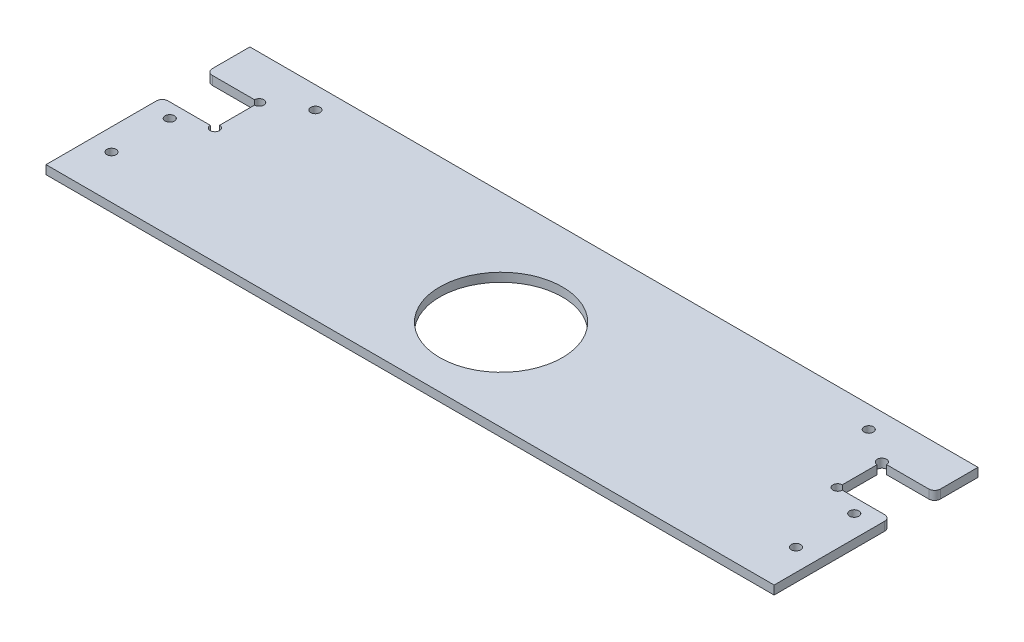
SolidWorks part; units mm, degrees
material "Thornel Mat VMA"
ref_plane "前视基准面" through (0, 0, 0) normal (0, 0, 1) x (1, 0, 0)
ref_plane "上视基准面" through (0, 0, 0) normal (0, 1, 0) x (1, 0, 0)
ref_plane "右视基准面" through (0, 0, 0) normal (1, 0, 0) x (0, 0, -1)
other "Configuration Table"
sketch "草图1" plane through (0, 0, 0) normal (0, 1, 0) x (1, 0, 0)
  line L1 (-125, -35) -> (125, -35)
  line L2 (-125, -35) -> (-125, 35)
  line L3 (-125, 35) -> (125, 35)
  line L4 (125, -35) -> (125, 35)
  line L5 (-125, -35) -> (125, 35) construction
  line L6 (-125, 35) -> (125, -35) construction
  point P0 (0, 0)
  dimension "D1" = 70
  dimension "D2" = 250
extrude "凸台-拉伸1" add sketch "草图1" along normal blind 3
sketch "草图2" plane through (0, 3, 0) normal (0, 1, 0) x (1, 0, 0)
  line L0 (-117.5, 35) -> (-117.5, -35) construction
  line L1 (125, 35) -> (-125, 35) construction
  line L2 (-125, -35) -> (125, -35) construction
  line L3 (-125, 27.5) -> (125, 27.5) construction
  line L4 (-125, 35) -> (-125, -35) construction
  line L5 (125, -35) -> (125, 35) construction
  line L6 (0, 0) -> (0, -35) construction
  circle A0 centre (-95, 27.5) radius 1.6
  circle A1 centre (95, 27.5) radius 1.6
  circle A2 centre (-117.5, 0) radius 1.6
  circle A3 centre (-117.5, -20) radius 1.6
  circle A4 centre (117.5, -20) radius 1.6
  circle A5 centre (117.5, 0) radius 1.6
  dimension "D3" = 3.2
  dimension "D4" = 3.2
  dimension "D5" = 3.2
  dimension "D6" = 3.2
  dimension "D7" = 30
  dimension "D8" = 30
  dimension "D9" = 35
  dimension "D10" = 20
  dimension "D1" = 7.5
  dimension "D2" = 7.5
extrude "切除-拉伸1" cut sketch "草图2" against normal through all
sketch "草图4" plane through (0, 3, 0) normal (0, 1, 0) x (1, 0, 0)
  line L0 (0, 0) -> (0, 35) construction
  line L1 (-125, 35) -> (-110.1, 35) construction
  line L2 (-125, 35) -> (-125, 20.1) construction
  line L3 (-125, 20.1) -> (-110.1, 20.1) construction
  line L4 (-110.1, 35) -> (-110.1, 20.1) construction
  line L5 (-125, 20.1) -> (-106.9, 20.1)
  line L6 (-125, 20.1) -> (-125, 4.9)
  line L7 (-125, 4.9) -> (-106.9, 4.9)
  line L8 (-106.9, 20.1) -> (-106.9, 4.9)
  line L9 (110.1, 35) -> (110.1, 20.1) construction
  line L10 (125, 20.1) -> (110.1, 20.1) construction
  line L11 (125, 35) -> (125, 20.1) construction
  line L12 (125, 35) -> (110.1, 35) construction
  line L13 (106.9, 20.1) -> (106.9, 4.9)
  line L14 (125, 4.9) -> (106.9, 4.9)
  line L15 (125, 20.1) -> (125, 4.9)
  line L16 (125, 20.1) -> (106.9, 20.1)
  dimension "D1" = 14.9
  dimension "D2" = 15.2
  dimension "D3" = 18.1
extrude "切除-拉伸3" cut sketch "草图4" against normal through all
fillet "圆角2" radius 2 4 edges at (125, 1.5, -20.1) (125, 1.5, -4.9) (-125, 1.5, -20.1) (-125, 1.5, -4.9)
sketch "草图5" plane through (0, 3, 0) normal (0, 1, 0) x (1, 0, 0)
  circle A0 centre (-106.9, 20.1) radius 1.6
  circle A1 centre (-106.9, 4.9) radius 1.6
  circle A2 centre (106.9, 4.9) radius 1.6
  circle A3 centre (106.9, 20.1) radius 1.6
  dimension "D1" = 3.2
  dimension "D2" = 3.2
  dimension "D3" = 3.2
  dimension "D4" = 3.2
extrude "切除-拉伸4" cut sketch "草图5" against normal through all
sketch "草图6" plane through (0, 3, 0) normal (0, 1, 0) x (1, 0, 0)
  line L0 (0, 35) -> (0, -35) construction
  line L1 (125, 35) -> (-125, 35) construction
  line L2 (-125, -35) -> (125, -35) construction
  circle A0 centre (0, -3.75) radius 21.05
  dimension "D1" = 42.1
  dimension "D2" = 38.75
extrude "切除-拉伸5" cut sketch "草图6" against normal through all
